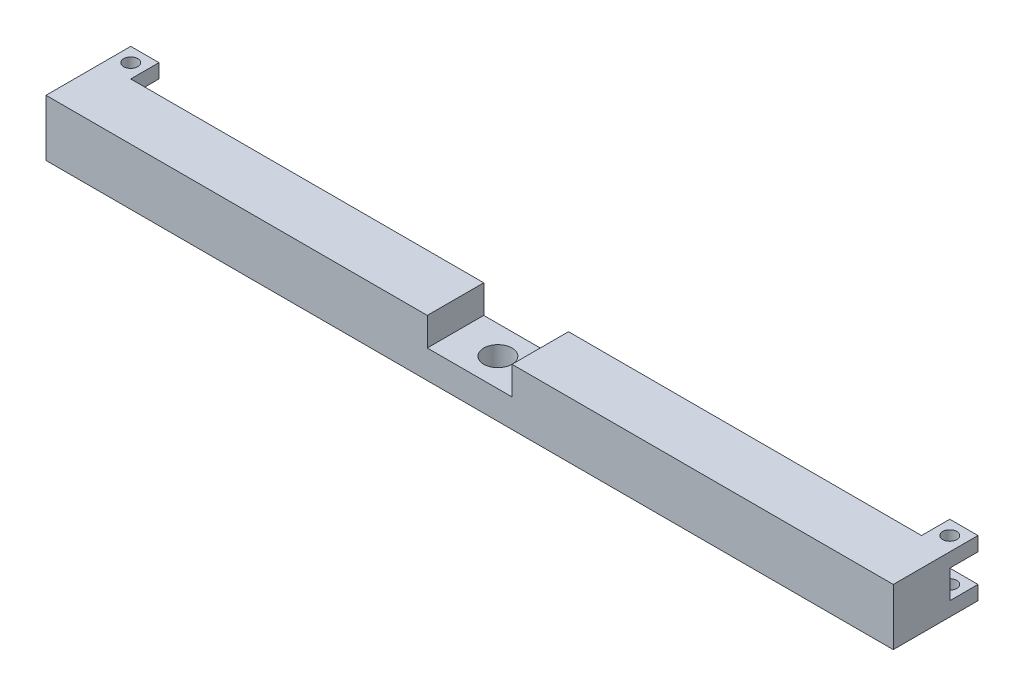
SolidWorks part; units mm, degrees
ref_plane "Front" through (0, 0, 0) normal (0, 0, 1) x (1, 0, 0)
ref_plane "Top" through (0, 0, 0) normal (0, 1, 0) x (1, 0, 0)
ref_plane "Right" through (0, 0, 0) normal (1, 0, 0) x (0, 0, -1)
sketch "Sketch1" plane through (0, 0, 0) normal (0, 1, 0) x (1, 0, 0)
  line L0 (0, -50) -> (0, 50) construction
  line L1 (-150, 10) -> (150, 10)
  line L2 (-150, 10) -> (-150, -10)
  line L3 (-150, -10) -> (150, -10)
  line L4 (150, 10) -> (150, -10)
  line L5 (-150, 10) -> (150, -10) construction
  line L6 (-150, -10) -> (150, 10) construction
  line L7 (-150, 10) -> (-140, 10)
  line L8 (-150, 10) -> (-150, 20)
  line L9 (-150, 20) -> (-140, 20)
  line L10 (-140, 10) -> (-140, 20)
  line L11 (140, 10) -> (140, 20)
  line L12 (150, 10) -> (150, 20)
  line L13 (150, 20) -> (140, 20)
  point P0 (0, 0)
  dimension "D1" = 300
  dimension "D2" = 20
  dimension "D3" = 10
  dimension "D4" = 10
extrude "Boss-Extrude1" add sketch "Sketch1" along normal blind 20 contours L4 L1 L2 L3 | L1 L10 L9 L8 | L12 L13 L11 L1
sketch "Sketch6" plane through (0, 0, -20) normal (0, 0, -1) x (-1, 0, 0)
  line L0 (-150, 20) -> (-150, 0) construction
  line L1 (-150, 15) -> (-140, 15)
  line L2 (-150, 15) -> (-150, 5)
  line L3 (-150, 5) -> (-140, 5)
  line L4 (-140, 15) -> (-140, 5)
  line L5 (-140, 20) -> (-140, 0) construction
  line L6 (-150, 20) -> (-140, 20) construction
  line L7 (0, 50) -> (0, -50) construction
  line L8 (140, 15) -> (140, 5)
  line L9 (150, 5) -> (140, 5)
  line L10 (150, 15) -> (150, 5)
  line L11 (150, 15) -> (140, 15)
  dimension "D1" = 5
  dimension "D2" = 10
extrude "Cut-Extrude5" cut sketch "Sketch6" against normal up to surface (10 mm away) up to face at (0, 10, -10)
sketch "Sketch2" plane through (0, 20, 0) normal (0, 1, 0) x (1, 0, 0)
  line L1 (-15, 10) -> (15, 10)
  line L2 (-15, 10) -> (-15, -10)
  line L3 (-15, -10) -> (15, -10)
  line L4 (15, 10) -> (15, -10)
  line L5 (-15, 10) -> (15, -10) construction
  line L6 (-15, -10) -> (15, 10) construction
  line L8 (-140, 10) -> (140, 10) construction
  point P0 (0, 0)
  dimension "D1" = 30
extrude "Cut-Extrude1" cut sketch "Sketch2" against normal blind 10
sketch "Sketch4" plane through (0, 20, 0) normal (0, 1, 0) x (1, 0, 0)
  line L1 (0, -50) -> (0, 50) construction
  line L4 (-150, 20) -> (-140, 20) construction
  line L5 (-140, 10) -> (-140, 20) construction
  circle A1 centre (-145, 15) radius 2.5
  circle A2 centre (145, 15) radius 2.5
  dimension "D1" = 5
  dimension "D2" = 5
  dimension "D3" = 5
extrude "Cut-Extrude3" cut sketch "Sketch4" against normal through all
sketch "Sketch5" plane through (0, 10, 0) normal (0, 1, 0) x (1, 0, 0)
  circle A0 centre (0, 0) radius 5
  dimension "D1" = 10
extrude "Cut-Extrude4" cut sketch "Sketch5" against normal up to next
